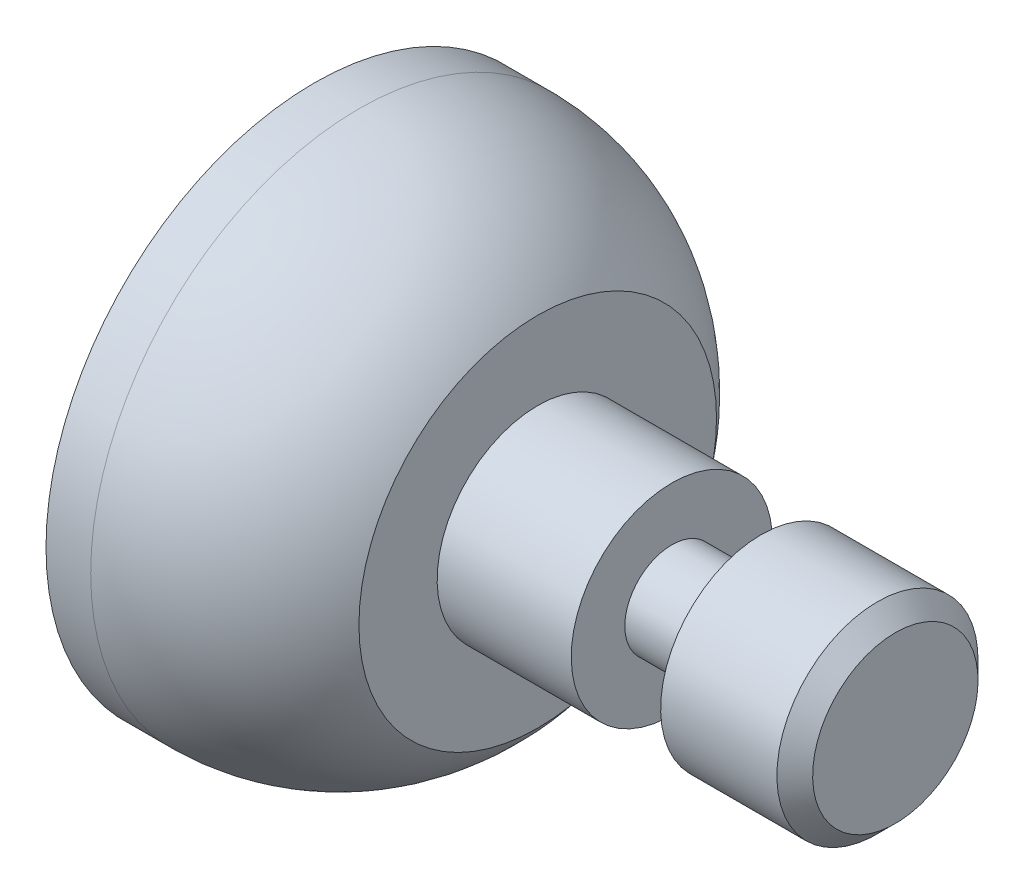
SolidWorks part; units mm, degrees
ref_plane "Front Plane" through (0, 0, 0) normal (0, 0, 1) x (1, 0, 0)
ref_plane "Top Plane" through (0, 0, 0) normal (0, 1, 0) x (1, 0, 0)
ref_plane "Right Plane" through (0, 0, 0) normal (1, 0, 0) x (0, 0, -1)
sketch "Sketch1" plane through (0, 0, 0) normal (0, 0, 1) x (1, 0, 0)
  line L0 (0, 0) -> (0, 19.05)
  line L1 (0, 19.05) -> (3.175, 19.05)
  line L2 (15.875, 12.7) -> (15.875, 7.1437)
  line L3 (15.875, 7.1437) -> (25.4, 7.1437)
  line L4 (25.4, 7.1437) -> (25.4, 3.3401)
  line L5 (25.4, 3.3401) -> (31.75, 3.3401)
  line L6 (31.75, 3.3401) -> (31.75, 7.1437)
  line L7 (31.75, 7.1437) -> (41.275, 7.1437)
  line L8 (41.275, 7.1437) -> (41.275, 0)
  line L9 (41.275, 0) -> (0, 0)
  arc A0 (3.175, 19.05) -> (15.875, 12.7) centre (3.175, 3.175) cw
  point P6 (45.3525, 0)
  dimension "D5" = 15.875
  dimension "D1" = 19.05
  dimension "D2" = 3.3401
  dimension "D3" = 7.1437
  dimension "D4" = 15.875
  dimension "D6" = 9.525
  dimension "D7" = 6.35
  dimension "D8" = 25.4
  dimension "D9" = 3.175
revolve "Revolve1" add sketch "Sketch1" angle 360 about L9
chamfer "Chamfer1" distance 1.27 angle 45 1 edges at (41.275, 7.1437, 0)
